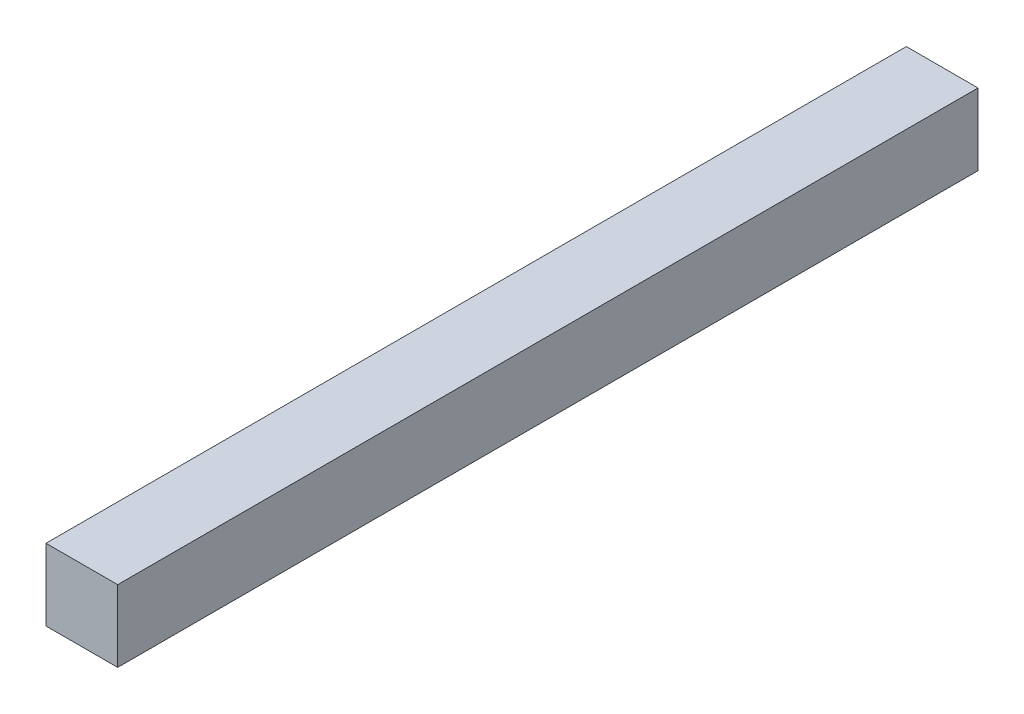
SolidWorks part; units mm, degrees
ref_plane "Front Plane" through (0, 0, 0) normal (0, 0, 1) x (1, 0, 0)
ref_plane "Top Plane" through (0, 0, 0) normal (0, 1, 0) x (1, 0, 0)
ref_plane "Right Plane" through (0, 0, 0) normal (1, 0, 0) x (0, 0, -1)
sketch "Sketch1" plane through (0, 0, 0) normal (0, 0, 1) x (1, 0, 0)
  line L1 (-66.4482, 23.9811) -> (-16.4482, 23.9811)
  line L2 (-66.4482, 23.9811) -> (-66.4482, -26.0189)
  line L3 (-66.4482, -26.0189) -> (-16.4482, -26.0189)
  line L4 (-16.4482, 23.9811) -> (-16.4482, -26.0189)
  dimension "D1" = 50
  dimension "D2" = 50
extrude "Boss-Extrude1" add sketch "Sketch1" along normal blind 600
